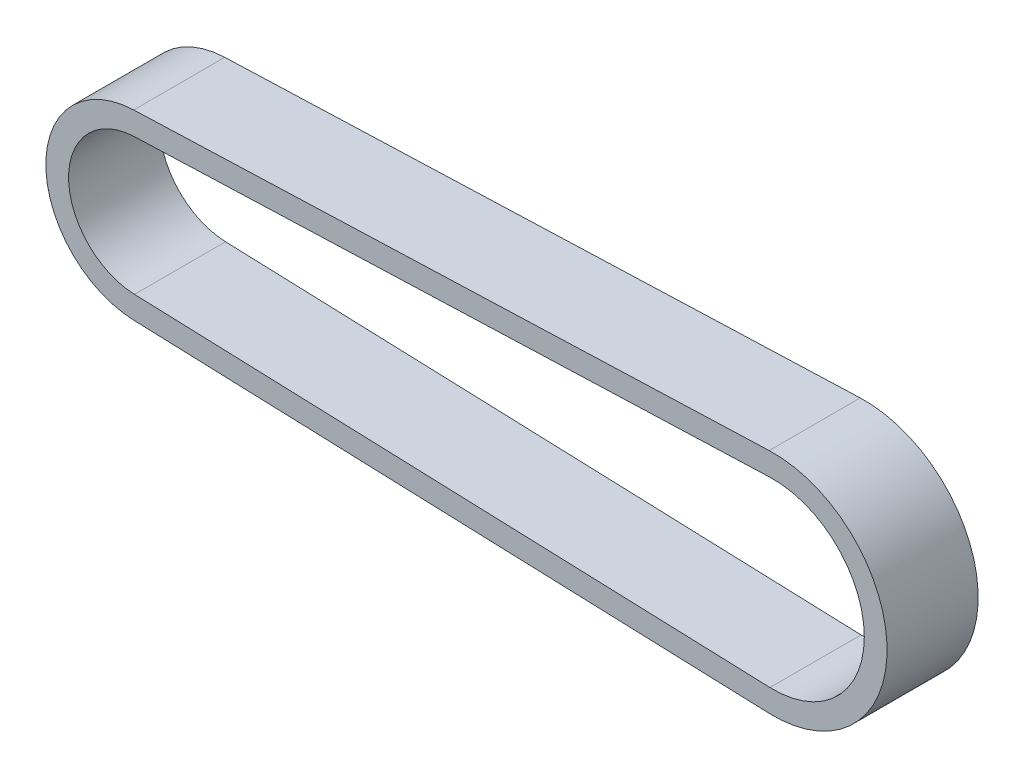
SolidWorks part; units mm, degrees
material "Rubber"
ref_plane "Front Plane" through (0, 0, 0) normal (0, 0, 1) x (1, 0, 0)
ref_plane "Top Plane" through (0, 0, 0) normal (0, 1, 0) x (1, 0, 0)
ref_plane "Right Plane" through (0, 0, 0) normal (1, 0, 0) x (0, 0, -1)
sketch "Sketch1" plane through (0, 0, 0) normal (0, 0, 1) x (1, 0, 0)
  line L0 (20.9277, 0.7495) -> (-20.9277, -0.7495)
  line L1 (-20.7487, -5.7463) -> (21.1603, -5.7463) construction
  line L4 (-20.9277, -10.7431) -> (20.9277, -12.2422)
  arc A0 (-20.9277, -0.7495) -> (-20.9277, -10.7431) centre (-20.7487, -5.7463) ccw
  arc A1 (20.9277, -12.2422) -> (20.9277, 0.7495) centre (21.1603, -5.7463) ccw
  dimension "D1" = 5
  dimension "D2" = 120
  dimension "D3" = 6.5
extrude "Extrude-Thin1" add sketch "Sketch1" along normal mid plane 6 thin
